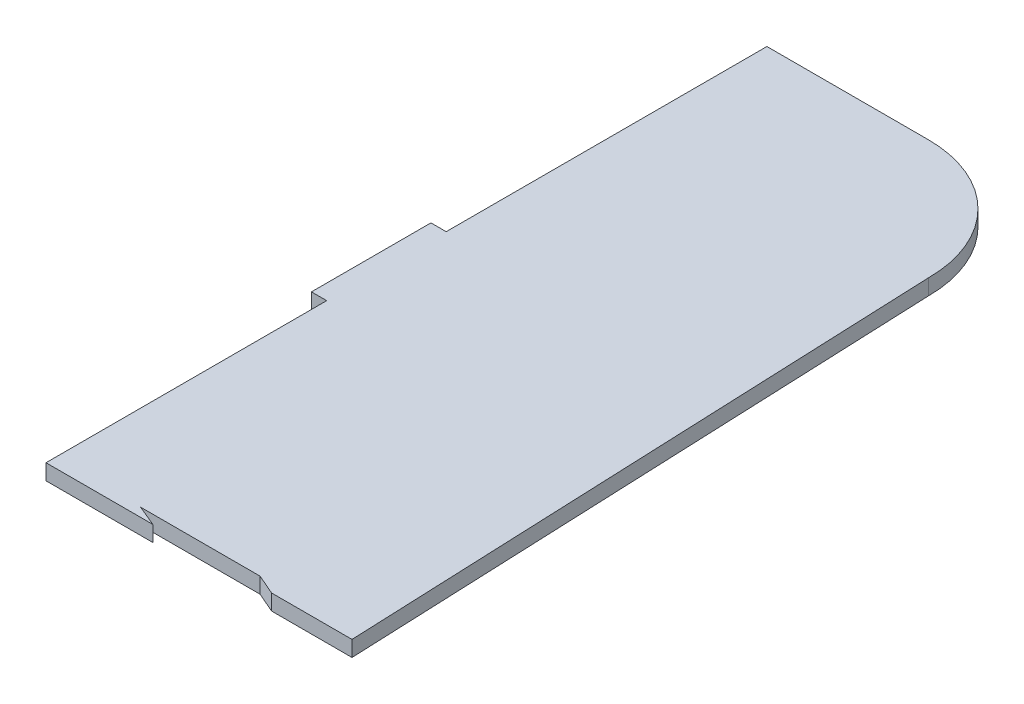
SolidWorks part; units mm, degrees
ref_plane "Front Plane" through (0, 0, 0) normal (0, 0, 1) x (1, 0, 0)
ref_plane "Top Plane" through (0, 0, 0) normal (0, 1, 0) x (1, 0, 0)
ref_plane "Right Plane" through (0, 0, 0) normal (1, 0, 0) x (0, 0, -1)
sketch "Sketch1" plane through (0, 0, 0) normal (0, 0, 1) x (1, 0, 0)
  line L1 (358.1218, 754.38) -> (137.9613, 754.38)
  line L2 (358.1218, 754.38) -> (562.8036, 754.38)
  line L3 (562.8036, 754.38) -> (562.8036, 744.38)
  line L4 (562.8036, 744.38) -> (137.9613, 744.38)
  line L5 (137.9613, 744.38) -> (137.9613, 754.38)
  dimension "D1" = 10
extrude "Boss-Extrude1" add sketch "Sketch1" along normal up to surface (459.74 mm away)
sketch "Sketch3" plane through (0, 744.38, 0) normal (0, -1, 0) x (1, 0, 0)
  line L0 (255.63, 0) -> (255.63, 459.74)
  line L1 (137.9613, 0) -> (562.8036, 0) construction
  line L2 (137.9613, 459.74) -> (562.8036, 459.74) construction
  line L3 (255.63, 459.74) -> (137.9613, 459.74)
  line L4 (137.9613, 459.74) -> (137.9613, 0)
  line L5 (137.9613, 0) -> (255.63, 0)
extrude "Cut-Extrude1" cut sketch "Sketch3" against normal blind 10
sketch "Sketch4" plane through (0, 754.38, 0) normal (0, 1, 0) x (1, 0, 0)
  line L0 (265.3552, -459.74) -> (265.3552, -280.7327)
  line L1 (562.8036, -459.74) -> (255.63, -459.74) construction
  line L2 (562.8036, 0) -> (255.63, 0) construction
  line L3 (265.3552, -459.74) -> (255.63, -459.74)
  line L4 (255.63, -459.74) -> (255.63, -280.7327)
  line L5 (203.1616, -280.7327) -> (265.3552, -280.7327) construction
  line L6 (203.1616, -204.5327) -> (265.3552, -204.5327) construction
  line L7 (265.3552, -459.74) -> (255.63, -459.74)
  line L8 (265.3552, -280.7327) -> (255.63, -280.7327)
  line L9 (265.3552, -204.5327) -> (255.63, -204.5327)
  line L10 (255.63, -204.5327) -> (255.63, 0)
  line L11 (265.3552, -204.5327) -> (265.3552, 0)
  line L12 (333.4642, -459.74) -> (369.7619, -561.8393)
  line L13 (333.4642, -459.74) -> (320.0538, -454.1127)
  line L14 (320.0538, -454.1127) -> (396.2538, -454.1127)
  line L15 (396.2538, -454.1127) -> (409.2168, -459.74)
  line L16 (409.2168, -459.74) -> (460.5019, -459.74)
  line L17 (460.5019, -459.74) -> (444.6051, -76.2)
  line L18 (369.7619, -561.8393) -> (604.2472, -525.6685)
  line L19 (604.2472, -525.6685) -> (681.4814, 161.1092)
  line L20 (681.4814, 161.1092) -> (358.7401, 101.8465)
  line L21 (358.7401, 101.8465) -> (368.4051, 0)
  line L23 (265.3552, 0) -> (255.63, 0)
  line L24 (255.63, -204.5327) -> (255.63, 0)
  arc A1 (444.6051, -76.2) -> (368.4051, 0) centre (368.4051, -76.2) ccw construction
  arc A2 (444.6051, -76.2) -> (368.4051, 0) centre (368.4051, -76.2) ccw
  line M2 (562.8036, 0) -> (255.63, 0)
  line M3 (255.63, 0) -> (255.63, -459.74)
  line M4 (255.63, -459.74) -> (562.8036, -459.74)
  line M5 (562.8036, -459.74) -> (562.8036, 0)
extrude "Cut-Extrude3" cut sketch "Sketch4" against normal blind 63 contours L0 L8 M3 M4 | L9 L11 M2 M3 | L20 L21 L12 L18 L19 M2 M5 M4
